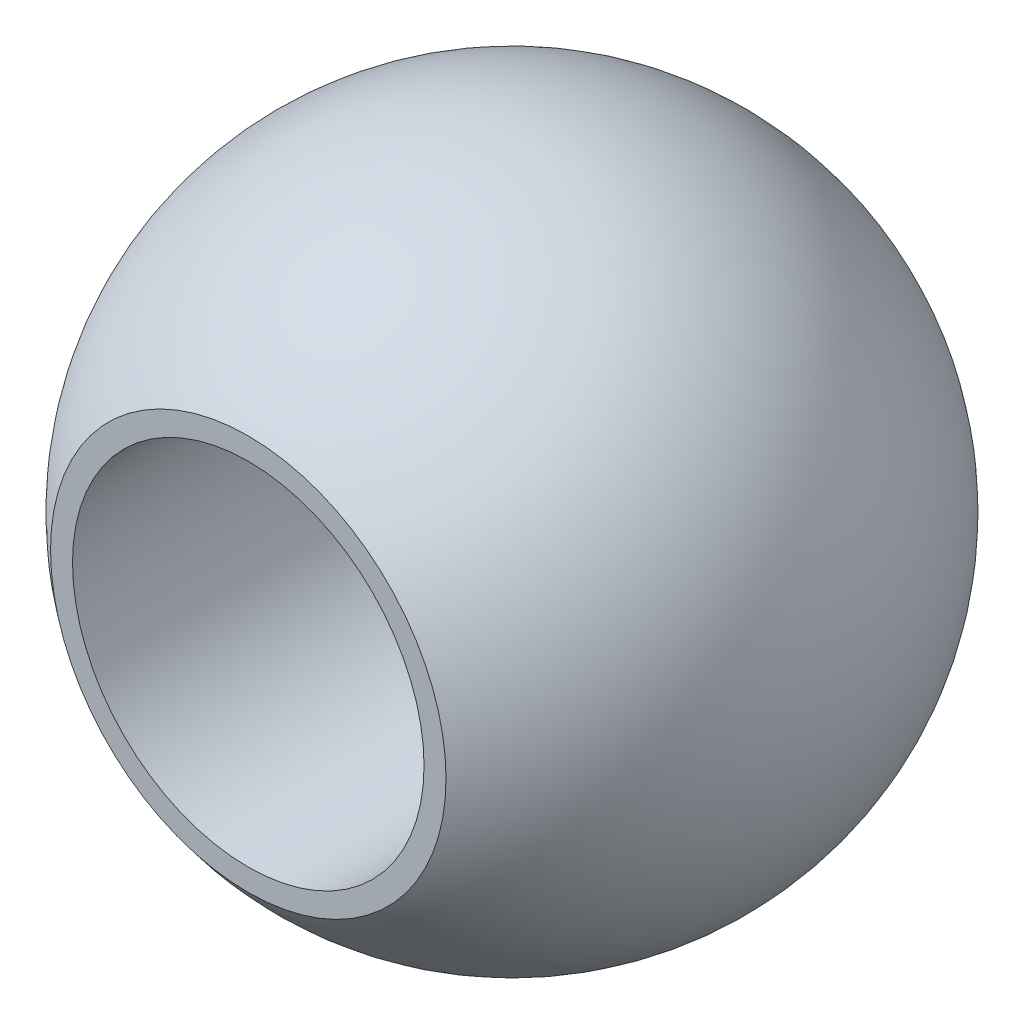
SolidWorks part; units mm, degrees
material "Легированная сталь (SS)"
ref_plane "Front Plane" through (0, 0, 0) normal (0, 0, 1) x (1, 0, 0)
ref_plane "Top Plane" through (0, 0, 0) normal (0, 1, 0) x (1, 0, 0)
ref_plane "Right Plane" through (0, 0, 0) normal (1, 0, 0) x (0, 0, -1)
sketch "Эскиз1" plane through (0, 0, 0) normal (0, 1, 0) x (1, 0, 0)
  line L0 (0, 7.5) -> (0, -7.5) construction
  line L1 (0, 6) -> (4.5, 6) construction
  line L2 (-7.5, 0) -> (7.5, 0) construction
  line L3 (0, -6) -> (4.5, -6) construction
  line L4 (4, 6) -> (4, -6)
  line L5 (4, 6) -> (4.5, 6)
  line L6 (4.5, -6) -> (4, -6)
  circle A0 centre (0, 0) radius 7.5 construction
  arc A1 (4.5, 6) -> (4.5, -6) centre (0, 0) cw
  dimension "D1" = 15
  dimension "D2" = 6
  dimension "D3" = 4
revolve "Повернуть1" add sketch "Эскиз1" angle 360 about L0
